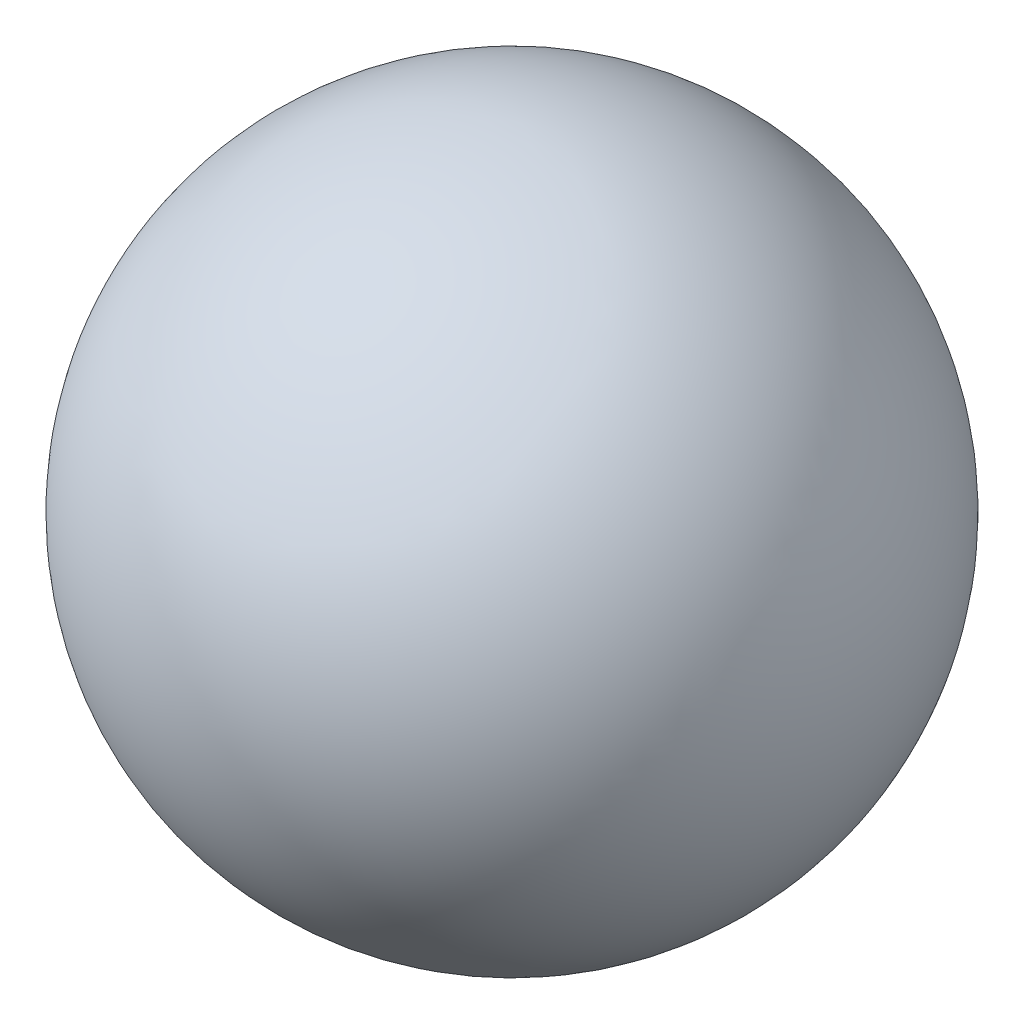
SolidWorks part; units mm, degrees
material "AISI 1020"
ref_plane "Plano superior" through (0, 0, 0) normal (0, 0, 1) x (1, 0, 0)
ref_plane "Plano frontal" through (0, 0, 0) normal (0, 1, 0) x (1, 0, 0)
ref_plane "Plano direito" through (0, 0, 0) normal (1, 0, 0) x (0, 0, -1)
sketch "Esboço1" plane through (0, 0, 0) normal (0, 1, 0) x (1, 0, 0)
  line L0 (5.9286, 0) -> (39.3263, 0) construction
  line L1 (46.6274, 0) -> (0, 0)
  line L3 (0, 8) -> (0, 0)
  arc A0 (46.6274, 0) -> (0, 8) centre (22.6274, 0) ccw
  point P5 (5.9286, -8)
  point P6 (77.652, -8)
  point P7 (5.9286, 8)
  point P8 (77.652, 8)
  dimension "D2" = 24
revolve "Revolução1" add sketch "Esboço1" angle 360 about L0
hole_wizard "Furo roscado de M12x1.51" positions "Esboço2" profile "Esboço3" tap size "M12x1.5" standard "DIN"
sketch "Esboço2" plane through (0, 0, 0) normal (-1, 0, 0) x (0, 0, 1)
  point P0 (0, 0)
sketch "Esboço3" plane through (0, 0, 0) normal (0, 1, 0) x (0, 0, 1)
  line L0 (0, 0) -> (0, 33.1545)
  line L1 (0, 33.1545) -> (5.25, 30)
  line L2 (5.25, 30) -> (5.25, 0.775)
  line L3 (5.25, 0.775) -> (6.025, 0)
  line L5 (6.025, 0) -> (0, 0)
  line L6 (-5.25, 0.775) -> (-6.025, 0) construction
  line L10 (0, 33.1545) -> (-5.25, 30) construction
  line L11 (0, -6.35) -> (0, 107.95) construction
  dimension "Tap Drill Dia." = 10.5
  dimension "Tap Drill Depth" = 30
  dimension "Near C'Sink Dia." = 12.05
  dimension "Near C'Sink Angle" = 90
  dimension "Drill Angle" = 118
cosmetic thread "Rosca de furo1" parameters "D1"=25, "D2"=12
